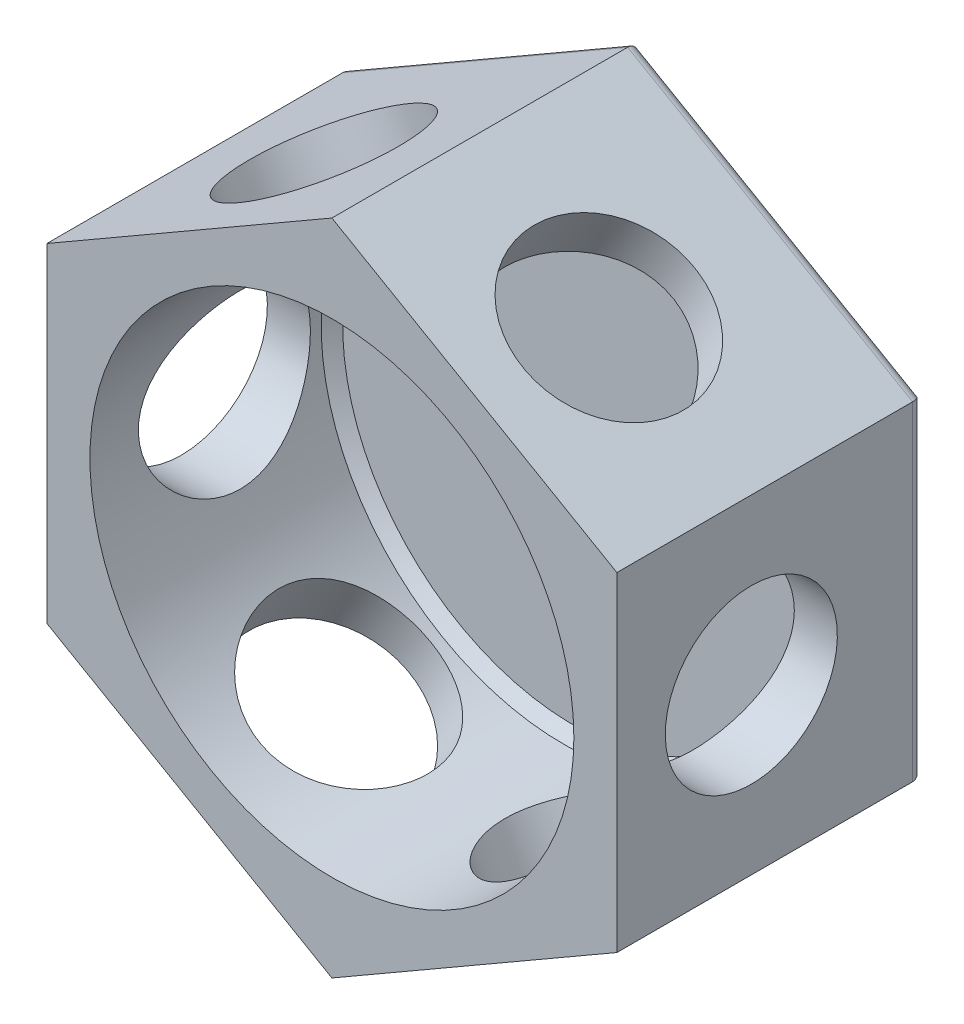
SolidWorks part; units mm, degrees
ref_plane "Front Plane" through (0, 0, 0) normal (0, 0, 1) x (1, 0, 0)
ref_plane "Top Plane" through (0, 0, 0) normal (0, 1, 0) x (1, 0, 0)
ref_plane "Right Plane" through (0, 0, 0) normal (1, 0, 0) x (0, 0, -1)
sketch "Sketch1" plane through (0, 0, 0) normal (0, 0, 1) x (1, 0, 0)
  line L1 (0, 61.1991) -> (-53, 30.5996)
  line L2 (-53, 30.5996) -> (-53, -30.5996)
  line L3 (-53, -30.5996) -> (0, -61.1991)
  line L4 (0, -61.1991) -> (53, -30.5996)
  line L5 (53, -30.5996) -> (53, 30.5996)
  line L6 (53, 30.5996) -> (0, 61.1991)
  circle A0 centre (0, 0) radius 53 construction
  point P1 (0, 0)
  point P10 (0, 0)
  point P11 (0, 0)
  dimension "D1" = 106
extrude "Boss-Extrude1" add sketch "Sketch1" along normal blind 25 and the other way blind 32
sketch "Sketch2" plane through (0, 0, 25) normal (0, 0, 1) x (1, 0, 0)
  circle A0 centre (0, 0) radius 45
  dimension "D1" = 90
extrude "Cut-Extrude1" cut sketch "Sketch2" against normal blind 45
sketch "Sketch3" plane through (26.5, -45.8993, 0) normal (0.5, -0.866, 0) x (0.866, 0.5, 0)
  circle A0 centre (0, 0) radius 16
  dimension "D1" = 32
extrude "Cut-Extrude2" cut sketch "Sketch3" against normal up to next
pattern_circular "CirPattern1" count 6 over 360 about axis through (0, 0, 25) along (0, 0, 1) of "Cut-Extrude2"
chamfer "Chamfer2" distance 2 angle 45 1 edges at (45, 0, -20)
fillet "Fillet1" radius 2 6 edges at (-26.5, 45.8993, -32) (-53, 0, -32) (-26.5, -45.8993, -32) (26.5, -45.8993, -32) (53, 0, -32) (26.5, 45.8993, -32)
